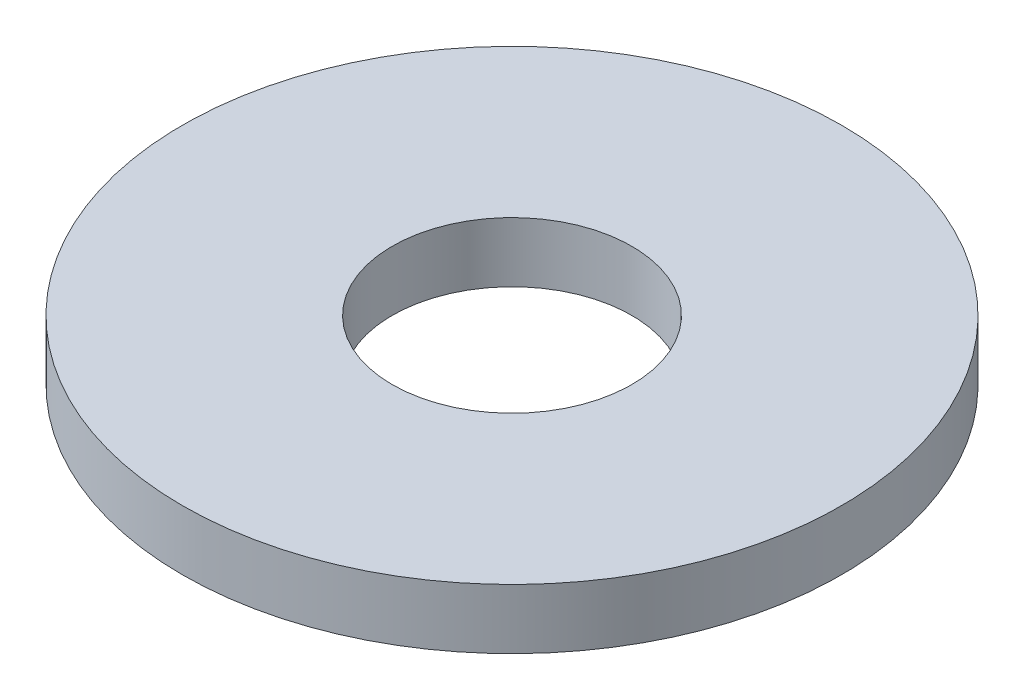
SolidWorks part; units mm, degrees
material "6061-T6 (SS)"
ref_plane "Front Plane" through (0, 0, 0) normal (0, 0, 1) x (1, 0, 0)
ref_plane "Top Plane" through (0, 0, 0) normal (0, 1, 0) x (1, 0, 0)
ref_plane "Right Plane" through (0, 0, 0) normal (1, 0, 0) x (0, 0, -1)
sketch "Sketch1" plane through (0, 0, 0) normal (0, 1, 0) x (1, 0, 0)
  circle A0 centre (0, 0) radius 6.35
  circle A1 centre (0, 0) radius 17.4625
  dimension "D1" = 12.7
  dimension "D2" = 34.925
extrude "Boss-Extrude1" add sketch "Sketch1" along normal blind 3.175
